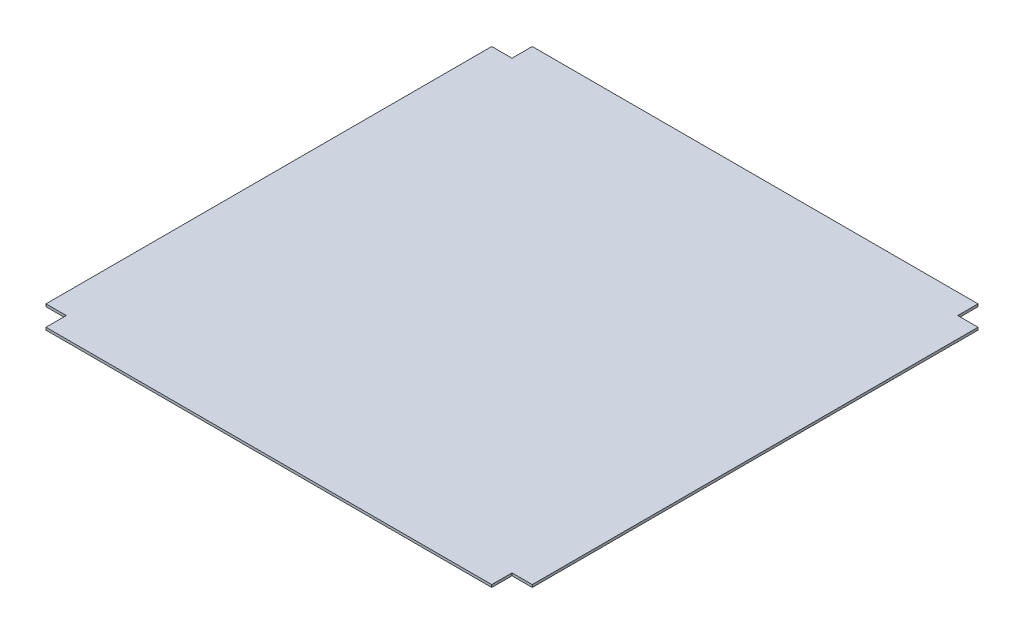
SolidWorks part; units mm, degrees
ref_plane "Front Plane" through (0, 0, 0) normal (0, 0, 1) x (1, 0, 0)
ref_plane "Top Plane" through (0, 0, 0) normal (0, 1, 0) x (1, 0, 0)
ref_plane "Right Plane" through (0, 0, 0) normal (1, 0, 0) x (0, 0, -1)
sketch "Sketch1" plane through (0, 0, 0) normal (0, 1, 0) x (1, 0, 0)
  line L1 (-609.6, -609.6) -> (609.6, -609.6)
  line L2 (-609.6, -609.6) -> (-609.6, 609.6)
  line L3 (-609.6, 609.6) -> (609.6, 609.6)
  line L4 (609.6, -609.6) -> (609.6, 609.6)
  line L5 (-609.6, -609.6) -> (609.6, 609.6) construction
  line L6 (-609.6, 609.6) -> (609.6, -609.6) construction
  point P0 (0, 0)
  dimension "D2" = 1219.2
  dimension "D1" = 1219.2
extrude "Boss-Extrude1" add sketch "Sketch1" along normal mid plane 6.35
sketch "Sketch2" plane through (0, 3.175, 0) normal (0, 1, 0) x (1, 0, 0)
  line L0 (0, 609.6) -> (0, -609.6) construction
  line L1 (-609.6, 609.6) -> (-558.8, 609.6)
  line L2 (-609.6, 609.6) -> (-609.6, 558.8)
  line L3 (-609.6, 558.8) -> (-558.8, 558.8)
  line L4 (-558.8, 609.6) -> (-558.8, 558.8)
  line L5 (609.6, 609.6) -> (-609.6, 609.6) construction
  line L6 (-609.6, -609.6) -> (609.6, -609.6) construction
  line L7 (609.6, 0) -> (-609.6, 0) construction
  line L8 (609.6, -609.6) -> (609.6, 609.6) construction
  line L9 (-609.6, 609.6) -> (-609.6, -609.6) construction
  line L10 (558.8, 609.6) -> (558.8, 558.8)
  line L11 (609.6, 558.8) -> (558.8, 558.8)
  line L12 (609.6, 609.6) -> (609.6, 558.8)
  line L13 (609.6, 609.6) -> (558.8, 609.6)
  line L14 (609.6, -609.6) -> (558.8, -609.6)
  line L15 (609.6, -609.6) -> (609.6, -558.8)
  line L16 (609.6, -558.8) -> (558.8, -558.8)
  line L17 (558.8, -609.6) -> (558.8, -558.8)
  line L18 (-558.8, -609.6) -> (-558.8, -558.8)
  line L19 (-609.6, -558.8) -> (-558.8, -558.8)
  line L20 (-609.6, -609.6) -> (-609.6, -558.8)
  line L21 (-609.6, -609.6) -> (-558.8, -609.6)
  dimension "D1" = 50.8
extrude "Cut-Extrude1" cut sketch "Sketch2" against normal through all
equation "\"width\"= 48in"
equation "\"length\"= 48in"
equation "\"square tubing width\"= 2in"
equation "\"D1@Sketch2\"=\"square tubing width\""
equation "\"D1@Sketch1\"=\"width\""
equation "\"D2@Sketch1\"=\"length\""
